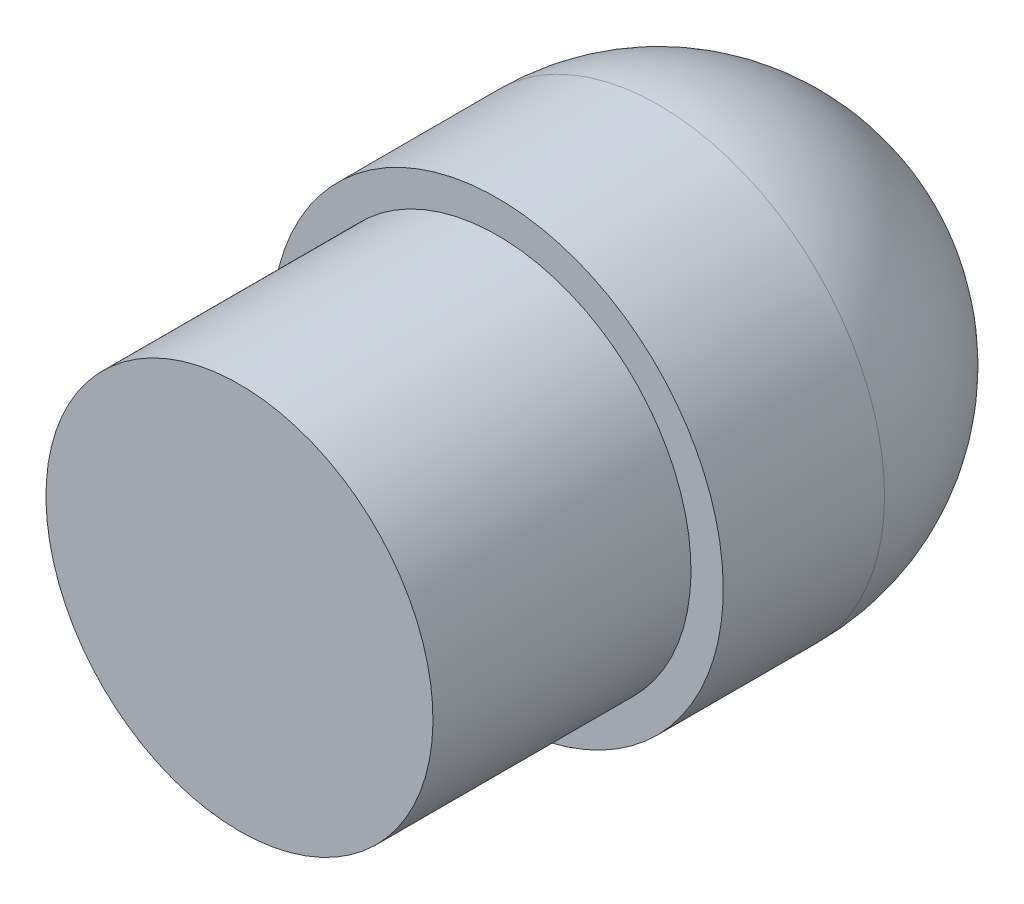
SolidWorks part; units mm, degrees
ref_plane "Front Plane" through (0, 0, 0) normal (0, 0, 1) x (1, 0, 0)
ref_plane "Top Plane" through (0, 0, 0) normal (0, 1, 0) x (1, 0, 0)
ref_plane "Right Plane" through (0, 0, 0) normal (1, 0, 0) x (0, 0, -1)
sketch "Sketch1" plane through (0, 0, 0) normal (1, 0, 0) x (0, 0, -1)
  line L0 (-25, 0) -> (-25, 15)
  line L1 (-25, 15) -> (-5, 15)
  line L2 (-5, 15) -> (-5, 17.5)
  line L3 (-5, 17.5) -> (7.5, 17.5)
  line L4 (-25, 0) -> (25, 0) construction
  line L5 (-25, 0) -> (25, 0)
  arc A0 (7.5, 17.5) -> (25, 0) centre (7.5, 0) cw
  point P7 (19.8744, 12.3744)
  point P8 (0, 0)
  dimension "D1" = 15
  dimension "D2" = 20
  dimension "D3" = 50
revolve "Revolve1" add sketch "Sketch1" angle 360 about L4
